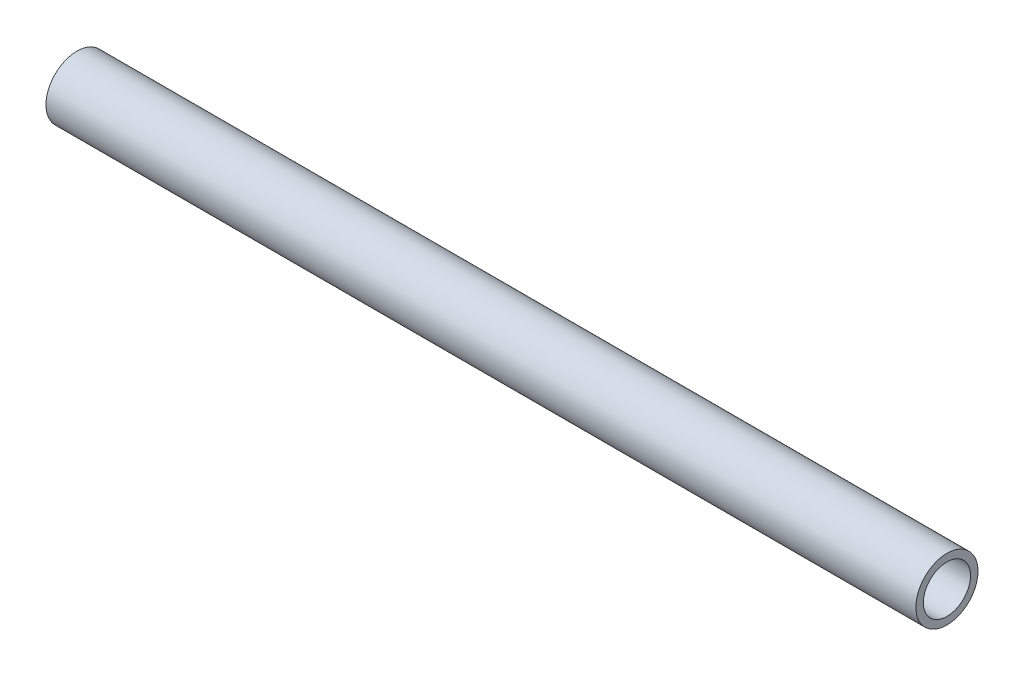
SolidWorks part; units mm, degrees
material "AISI 1010 Steel, hot rolled bar"
ref_plane "Front Plane" through (0, 0, 0) normal (0, 0, 1) x (1, 0, 0)
ref_plane "Top Plane" through (0, 0, 0) normal (0, 1, 0) x (1, 0, 0)
ref_plane "Right Plane" through (0, 0, 0) normal (1, 0, 0) x (0, 0, -1)
sketch "Sketch1" plane through (0, 0, 0) normal (1, 0, 0) x (0, 0, -1)
  circle A0 centre (0, 0) radius 12.7
  circle A1 centre (0, 0) radius 9.652
  dimension "D1" = 25.4
  dimension "D2" = 19.304
extrude "Boss-Extrude1" add sketch "Sketch1" along normal blind 355.6
